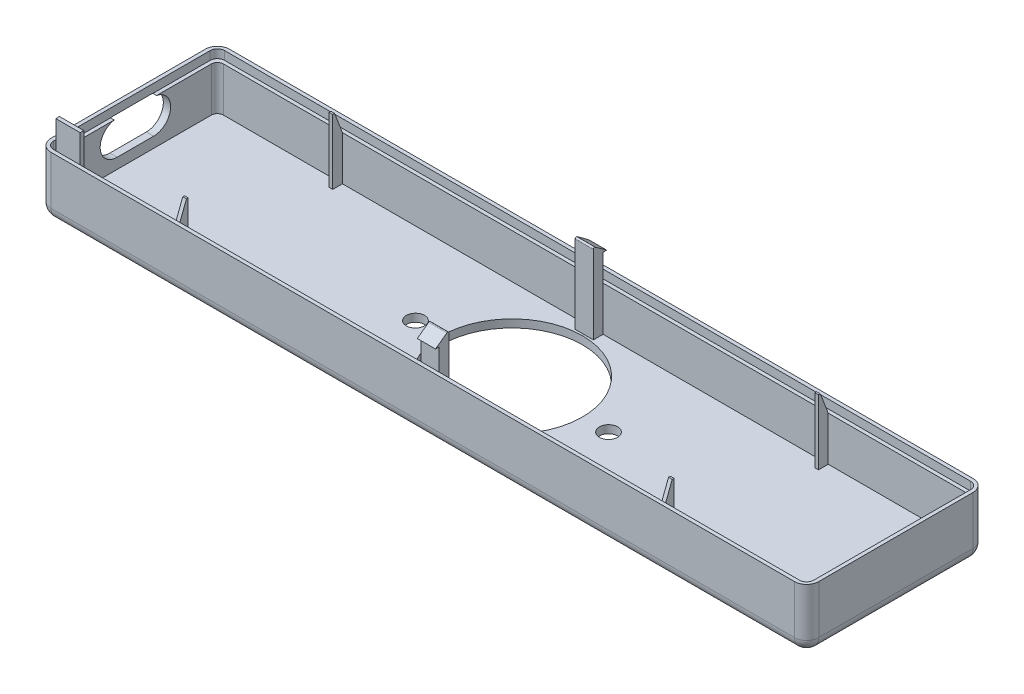
SolidWorks part; units mm, degrees
ref_plane "Front Plane" through (0, 0, 0) normal (0, 0, 1) x (1, 0, 0)
ref_plane "Top Plane" through (0, 0, 0) normal (0, 1, 0) x (1, 0, 0)
ref_plane "Right Plane" through (0, 0, 0) normal (1, 0, 0) x (0, 0, -1)
sketch "Sketch1" plane through (0, 0, 0) normal (0, 1, 0) x (1, 0, 0)
  line L1 (-80.2894, -18.669) -> (80.2894, -18.669)
  line L2 (-80.2894, -18.669) -> (-80.2894, 18.669)
  line L3 (-80.2894, 18.669) -> (80.2894, 18.669)
  line L4 (80.2894, -18.669) -> (80.2894, 18.669)
  line L5 (-80.2894, -18.669) -> (80.2894, 18.669) construction
  line L6 (-80.2894, 18.669) -> (80.2894, -18.669) construction
  point P0 (0, 0)
  dimension "D1" = 160.5788
  dimension "D2" = 37.338
extrude "Boss-Extrude1" add sketch "Sketch1" along normal blind 12.7
sketch "Sketch2" plane through (0, 12.7, 0) normal (0, 1, 0) x (1, 0, 0)
  line L0 (-80.2894, 18.669) -> (-80.2894, -18.669) construction
  line L1 (-78.7654, 17.145) -> (78.7654, 17.145)
  line L2 (-78.7654, 17.145) -> (-78.7654, -17.145)
  line L3 (-78.7654, -17.145) -> (78.7654, -17.145)
  line L4 (78.7654, 17.145) -> (78.7654, -17.145)
  line L5 (-78.7654, 17.145) -> (78.7654, -17.145) construction
  line L6 (-78.7654, -17.145) -> (78.7654, 17.145) construction
  line L7 (-80.2894, -18.669) -> (80.2894, -18.669) construction
  point P0 (0, 0)
  dimension "D1" = 1.524
  dimension "D2" = 1.524
extrude "Cut-Extrude3" cut sketch "Sketch2" against normal offset from surface (11.049 mm away) 1.651 up to face at (0, 0, 0)
fillet "Fillet1" radius 2.54 8 edges at (80.2894, 0, 0) (80.2894, 6.35, -18.669) (0, 0, -18.669) (0, 0, 18.669) (-80.2894, 0, 0) (-80.2894, 6.35, -18.669) (-80.2894, 6.35, 18.669) (80.2894, 6.35, 18.669)
fillet "Fillet2" radius 1.27 4 edges at (78.7654, 7.1755, -17.145) (78.7654, 7.1755, 17.145) (-78.7654, 7.1755, -17.145) (-78.7654, 7.1755, 17.145)
sketch "Sketch3" plane through (-80.2894, 0, 0) normal (-1, 0, 0) x (0, 0, 1)
  line L0 (3.81, 7.4193) -> (-3.81, 7.4193) construction
  line L1 (3.81, 3.8633) -> (-3.81, 3.8633)
  line L2 (3.81, 10.9753) -> (-3.81, 10.9753)
  line L3 (-16.129, 12.7) -> (16.129, 12.7) construction
  line L4 (0, 12.7) -> (0, -3.1618) construction
  arc A0 (3.81, 3.8633) -> (3.81, 10.9753) centre (3.81, 7.4193) ccw
  arc A1 (-3.81, 10.9753) -> (-3.81, 3.8633) centre (-3.81, 7.4193) ccw
  point P2 (0, 7.4193)
  dimension "D1" = 3.556
  dimension "D2" = 7.62
  dimension "D3" = 1.7247
extrude "Cut-Extrude4" cut sketch "Sketch3" against normal up to next
sketch "Sketch4" plane through (0, 12.7, 0) normal (0, 1, 0) x (1, 0, 0)
  line L0 (-80.2894, 16.129) -> (-80.2894, -16.129) construction
  line L1 (-79.5274, -17.907) -> (79.5274, -17.907)
  line L2 (-79.5274, -17.907) -> (-79.5274, 17.907)
  line L3 (-79.5274, 17.907) -> (79.5274, 17.907)
  line L4 (79.5274, -17.907) -> (79.5274, 17.907)
  line L5 (77.7494, 18.669) -> (-77.7494, 18.669) construction
  line L6 (80.2894, -16.129) -> (80.2894, 16.129) construction
  line L7 (-77.7494, -18.669) -> (77.7494, -18.669) construction
  dimension "D1" = 0.762
  dimension "D2" = 0.762
  dimension "D3" = 0.762
  dimension "D4" = 0.762
extrude "Cut-Extrude5" cut sketch "Sketch4" against normal blind 1.778
fillet "Fillet3" radius 1.524 4 edges at (79.5274, 11.811, -17.907) (-79.5274, 11.811, -17.907) (-79.5274, 11.811, 17.907) (79.5274, 11.811, 17.907)
sketch "Sketch5" plane through (0, 10.922, 0) normal (0, 1, 0) x (1, 0, 0)
  line L0 (-78.0034, -17.907) -> (78.0034, -17.907) construction
  line L1 (-72.4154, -17.907) -> (-77.4954, -17.907)
  line L2 (-72.4154, -17.907) -> (-72.4154, -17.145)
  line L3 (-72.4154, -17.145) -> (-77.4954, -17.145)
  line L4 (-77.4954, -17.907) -> (-77.4954, -17.145)
  line L5 (-77.4954, -17.145) -> (77.4954, -17.145) construction
  dimension "D1" = 5.08
extrude "Boss-Extrude2" add sketch "Sketch5" along normal blind 7.62
sketch "Sketch6" plane through (0, 1.651, 0) normal (0, 1, 0) x (1, 0, 0)
  line L0 (77.4954, 17.145) -> (-77.4954, 17.145) construction
  line L1 (-53.3654, 17.145) -> (-52.6034, 17.145)
  line L2 (-53.3654, 17.145) -> (-53.3654, 15.113)
  line L3 (-53.3654, 15.113) -> (-52.6034, 15.113)
  line L4 (-52.6034, 17.145) -> (-52.6034, 15.113)
  line L5 (-78.7654, 15.875) -> (-78.7654, -15.875) construction
  dimension "D1" = 0.762
  dimension "D2" = 2.032
  dimension "D3" = 25.4
extrude "Boss-Extrude3" add sketch "Sketch6" along normal offset from surface (13.589 mm away) 2.54 up to face at (-14.9911, 12.7, 3.5814) offset beyond the face yes
pattern_linear "LPattern1" count 2 spacing 101.6 along (1, 0, 0) count 2 spacing 32.258 along (0, 0, 1) of "Boss-Extrude3"
sketch "Sketch7" plane through (48.9966, 0, 0) normal (1, 0, 0) x (0, 0, -1)
  line L0 (17.145, 10.922) -> (15.494, 15.24)
  line L1 (17.145, 15.24) -> (15.113, 15.24) construction
  line L2 (15.494, 15.24) -> (17.145, 15.24)
  line L3 (17.145, 15.24) -> (17.145, 10.922)
  dimension "D1" = 0.381
extrude "Cut-Extrude6" cut sketch "Sketch7" against normal up to surface (102.362 mm away) up to face at (-53.3654, 8.9408, -16.3322)
mirror "Mirror1" about plane through (0, 0, 0) normal (0, 0, 1) of "Cut-Extrude6"
sketch "Sketch8" plane through (0, 1.651, 0) normal (0, 1, 0) x (1, 0, 0)
  line L0 (0, 0) -> (0, 21.7842) construction
  line L1 (1.905, -17.145) -> (-1.905, -17.145)
  line L2 (1.905, -17.145) -> (1.905, -15.113)
  line L3 (1.905, -15.113) -> (-1.905, -15.113)
  line L4 (-1.905, -17.145) -> (-1.905, -15.113)
  line L5 (1.905, 15.113) -> (-1.905, 15.113)
  line L6 (1.905, 15.113) -> (1.905, 17.145)
  line L7 (1.905, 17.145) -> (-1.905, 17.145)
  line L8 (-1.905, 15.113) -> (-1.905, 17.145)
  line L9 (-52.6034, -17.145) -> (48.2346, -17.145) construction
  line L10 (48.2346, 17.145) -> (-52.6034, 17.145) construction
  dimension "D1" = 3.81
  dimension "D2" = 2.032
extrude "Boss-Extrude4" add sketch "Sketch8" along normal offset from surface (14.859 mm away) 3.81 up to face at (-14.9911, 12.7, 3.5814) offset beyond the face yes
sketch "Sketch9" plane through (1.905, 0, 0) normal (1, 0, 0) x (0, 0, -1)
  line L0 (-15.113, 16.51) -> (-17.907, 16.51)
  line L1 (-17.907, 16.51) -> (-15.113, 18.542)
  line L2 (-15.113, 18.542) -> (-15.113, 16.51)
  line L3 (-17.145, 16.51) -> (-17.145, 10.922) construction
  dimension "D1" = 0.762
  dimension "D2" = 2.032
extrude "Boss-Extrude9" add sketch "Sketch9" against normal blind 3.81
fillet "Fillet4" radius 0.254 1 edges at (0, 18.542, 15.113)
mirror "Mirror2" about plane through (0, 0, 0) normal (0, 0, 1) of "Fillet4", "Boss-Extrude9"
sketch "Sketch10" plane through (0, 0, 0) normal (0, -1, 0) x (1, 0, 0)
  line L0 (-20.193, 0) -> (20.193, 0) construction
  circle A0 centre (0, 0) radius 14.732
  circle A1 centre (-20.193, 0) radius 1.905
  circle A2 centre (20.193, 0) radius 1.905
  dimension "D1" = 29.464
  dimension "D3" = 3.81
  dimension "D4" = 3.81
  dimension "D2" = 40.386
extrude "Cut-Extrude7" cut sketch "Sketch10" against normal through all
